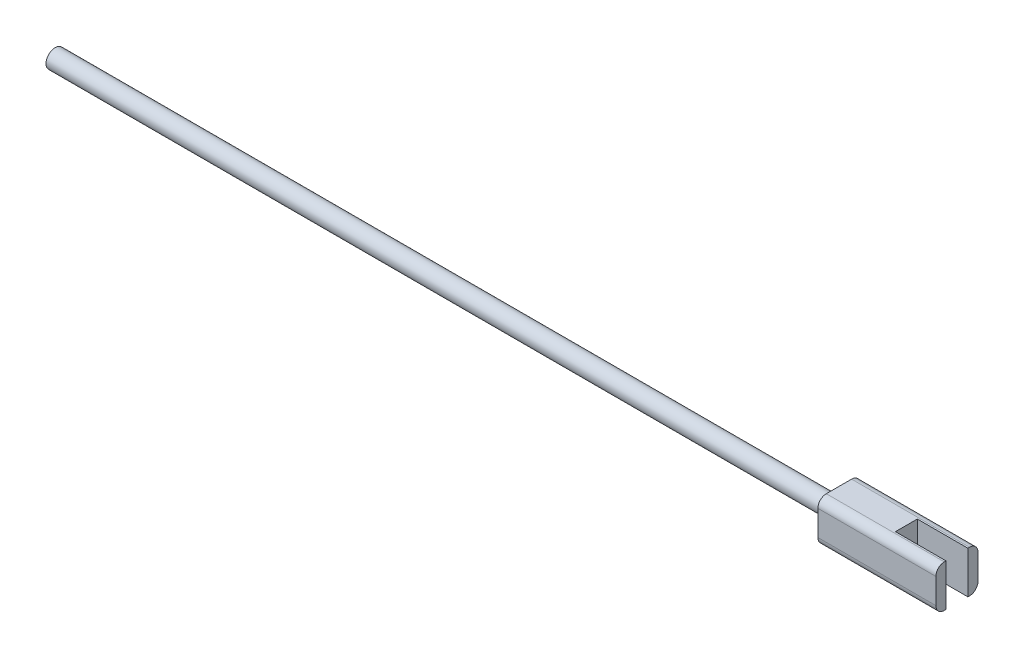
SolidWorks part; units mm, degrees
ref_plane "Front Plane" through (0, 0, 0) normal (0, 0, 1) x (1, 0, 0)
ref_plane "Top Plane" through (0, 0, 0) normal (0, 1, 0) x (1, 0, 0)
ref_plane "Right Plane" through (0, 0, 0) normal (1, 0, 0) x (0, 0, -1)
sketch "Sketch1" plane through (0, 0, 0) normal (1, 0, 0) x (0, 0, -1)
  circle A0 centre (0, 0) radius 1.09
extrude "Boss-Extrude1" add sketch "Sketch1" along normal blind 95.007
ref_plane "Plane1" through (93.007, 0, 0) normal (1, 0, 0) x (0, 0, -1)
sketch "Sketch2" plane through (93.007, 0, 0) normal (1, 0, 0) x (0, 0, -1)
  line L0 (-1.5, -2.5) -> (1.5, -2.5)
  line L1 (2.5, -1.5) -> (2.5, 1.5)
  line L2 (1.5, 2.5) -> (-1.5, 2.5)
  line L3 (-2.5, 1.5) -> (-2.5, -1.5)
  arc A0 (1.5, -2.5) -> (2.5, -1.5) centre (1.5, -1.5) ccw
  arc A1 (2.5, 1.5) -> (1.5, 2.5) centre (1.5, 1.5) ccw
  arc A2 (-1.5, 2.5) -> (-2.5, 1.5) centre (-1.5, 1.5) ccw
  arc A3 (-2.5, -1.5) -> (-1.5, -2.5) centre (-1.5, -1.5) ccw
extrude "Boss-Extrude2" add sketch "Sketch2" along normal blind 14
sketch "Sketch3" plane through (0, 0, 0) normal (0, 1, 0) x (1, 0, 0)
  line L0 (101.007, 1.3) -> (108.007, 1.3)
  line L1 (108.007, 1.3) -> (108.007, -1.3)
  line L2 (108.007, -1.3) -> (101.007, -1.3)
  line L3 (101.007, -1.3) -> (101.007, 1.3)
extrude "Cut-Extrude1" cut sketch "Sketch3" against normal through all and the other way through all
